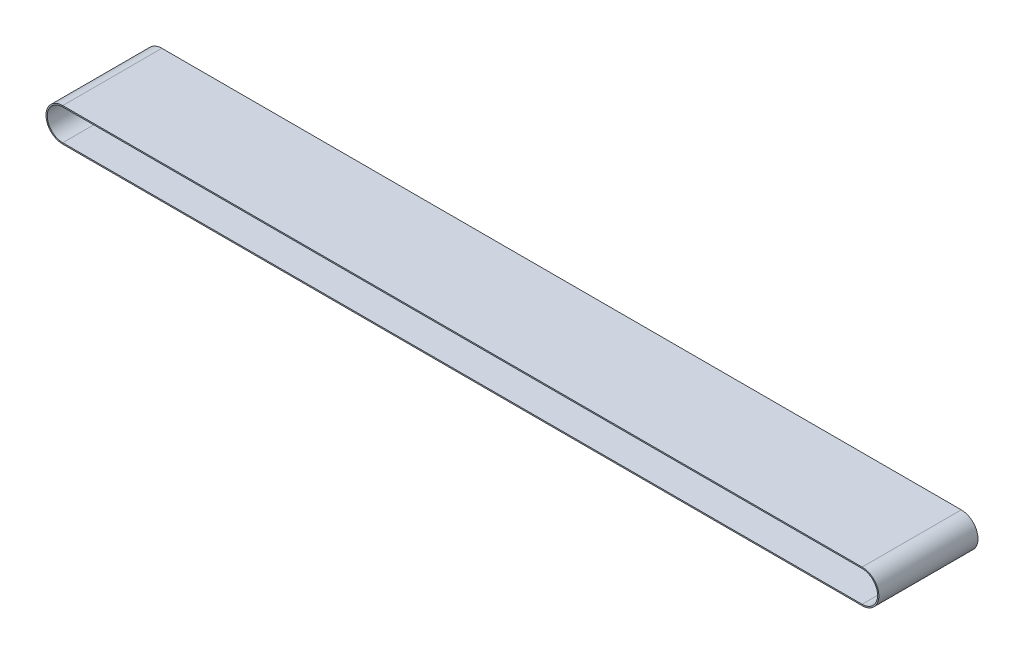
SolidWorks part; units mm, degrees
material "BUTYL"
ref_plane "Front Plane" through (0, 0, 0) normal (0, 0, 1) x (1, 0, 0)
ref_plane "Top Plane" through (0, 0, 0) normal (0, 1, 0) x (1, 0, 0)
ref_plane "Right Plane" through (0, 0, 0) normal (1, 0, 0) x (0, 0, -1)
sketch "Sketch1" plane through (0, 0, 0) normal (0, 0, 1) x (1, 0, 0)
  line L0 (-645, 27) -> (645, 27)
  line L1 (-645, 25) -> (645, 25)
  line L2 (-645, 25) -> (-645, -25) construction
  line L3 (-645, -25) -> (645, -25)
  line L4 (645, 25) -> (645, -25) construction
  line L5 (-645, 25) -> (645, -25) construction
  line L6 (-645, -25) -> (645, 25) construction
  line L7 (-645, -27) -> (645, -27)
  arc A0 (-645, 25) -> (-645, -25) centre (-645, 0) ccw
  arc A1 (645, -25) -> (645, 25) centre (645, 0) ccw
  arc A2 (645, -27) -> (645, 27) centre (645, 0) ccw
  arc A3 (-645, 27) -> (-645, -27) centre (-645, 0) ccw
  point P0 (0, 0)
  dimension "D1" = 1290
  dimension "D2" = 50
  dimension "D3" = 2
extrude "Boss-Extrude1" add sketch "Sketch1" along normal blind 160
